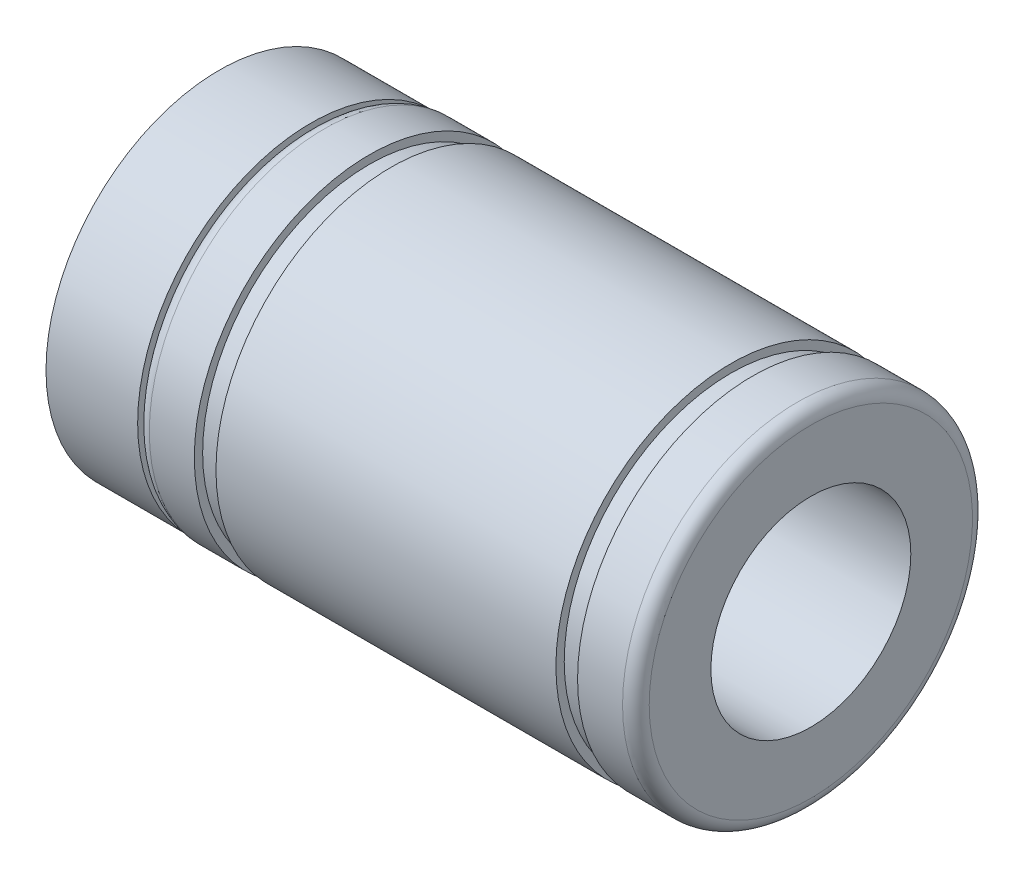
SolidWorks part; units mm, degrees
material "Cast Stainless Steel"
ref_plane "Front Plane" through (0, 0, 0) normal (0, 0, 1) x (1, 0, 0)
ref_plane "Top Plane" through (0, 0, 0) normal (0, 1, 0) x (1, 0, 0)
ref_plane "Right Plane" through (0, 0, 0) normal (1, 0, 0) x (0, 0, -1)
ref_plane "Plane1" through (0, 0, 0) normal (0, 0, 1) x (1, 0, 0)
sketch "Sketch1" plane through (0, 0, 0) normal (0, 0, 1) x (1, 0, 0)
  line L0 (-15, 9.7) -> (-15, 6)
  line L1 (-15, 6) -> (15, 6)
  line L2 (15, 6) -> (15, 9.7)
  line L3 (14.2, 10.5) -> (11.5, 10.5)
  line L4 (11.5, 10.5) -> (11.5, 10)
  line L5 (11.5, 10) -> (10.2, 10)
  line L6 (10.2, 10) -> (10.2, 10.5)
  line L7 (10.2, 10.5) -> (-10.2, 10.5)
  line L8 (-10.2, 10.5) -> (-10.2, 10)
  line L9 (-10.2, 10) -> (-11.5, 10)
  line L10 (-11.5, 10) -> (-11.5, 10.5)
  line L11 (-11.5, 10.5) -> (-14.2, 10.5)
  line L12 (15, 0) -> (-15, 0) construction
  arc A0 (15, 9.7) -> (14.2, 10.5) centre (14.2, 9.7) ccw
  arc A1 (-14.2, 10.5) -> (-15, 9.7) centre (-14.2, 9.7) ccw
revolve "Revolve1" add sketch "Sketch1" angle 360 about L12
ref_plane "Plane2" through (0, 0, 0) normal (0, 0, 1) x (1, 0, 0)
sketch "Sketch2" plane through (0, 0, 0) normal (0, 0, 1) x (1, 0, 0)
  line L0 (-20.5, 6) -> (-15, 6)
  line L1 (-15, 6) -> (-15, 10.4)
  line L2 (-15, 10.4) -> (-20.5, 10.4)
  line L3 (-20.5, 10.4) -> (-20.5, 6)
  line L4 (-15, 0) -> (-20.5, 0) construction
revolve "Revolve2" add sketch "Sketch2" angle 360 about L4
